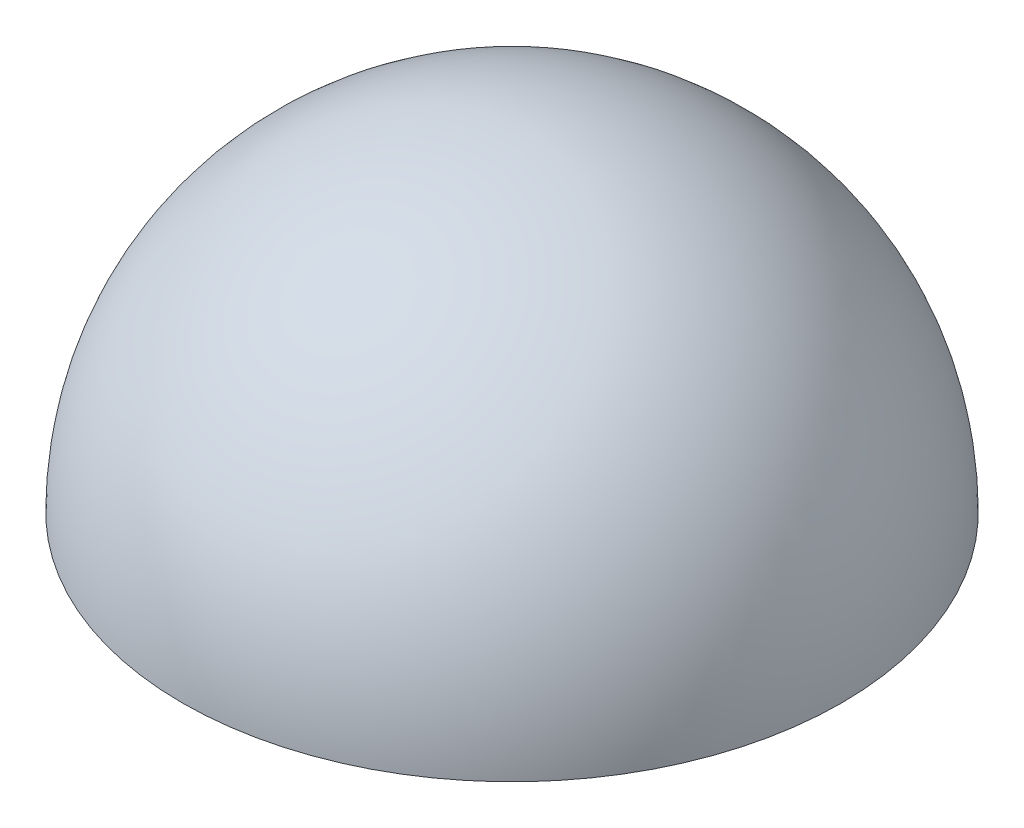
SolidWorks part; units mm, degrees
ref_plane "Front Plane" through (0, 0, 0) normal (0, 0, 1) x (1, 0, 0)
ref_plane "Top Plane" through (0, 0, 0) normal (0, 1, 0) x (1, 0, 0)
ref_plane "Right Plane" through (0, 0, 0) normal (1, 0, 0) x (0, 0, -1)
sketch "Sketch1" plane through (0, 0, 0) normal (0, 0, 1) x (1, 0, 0)
  line L0 (0, 0) -> (0, -87.884)
  line L1 (0, 0) -> (-37.084, 0)
  line L2 (0, 0) -> (0, 37.084)
  line L3 (0, -87.884) -> (-37.084, -87.884)
  line L4 (0, -87.884) -> (0, -124.968)
  line L5 (-37.084, 0) -> (-37.084, -87.884)
  line L6 (-25.4, 0) -> (-25.4, -87.884)
  arc A0 (0, 37.084) -> (-37.084, 0) centre (0, 0) ccw
  arc A1 (-37.084, -87.884) -> (0, -124.968) centre (0, -87.884) ccw
  dimension "D1" = 87.884
  dimension "D2" = 37.084
  dimension "D3" = 37.084
  dimension "D4" = 37.084
  dimension "D5" = 37.084
  dimension "D6" = 25.4
revolve "Revolve1" add sketch "Sketch1" angle 360 about L2
